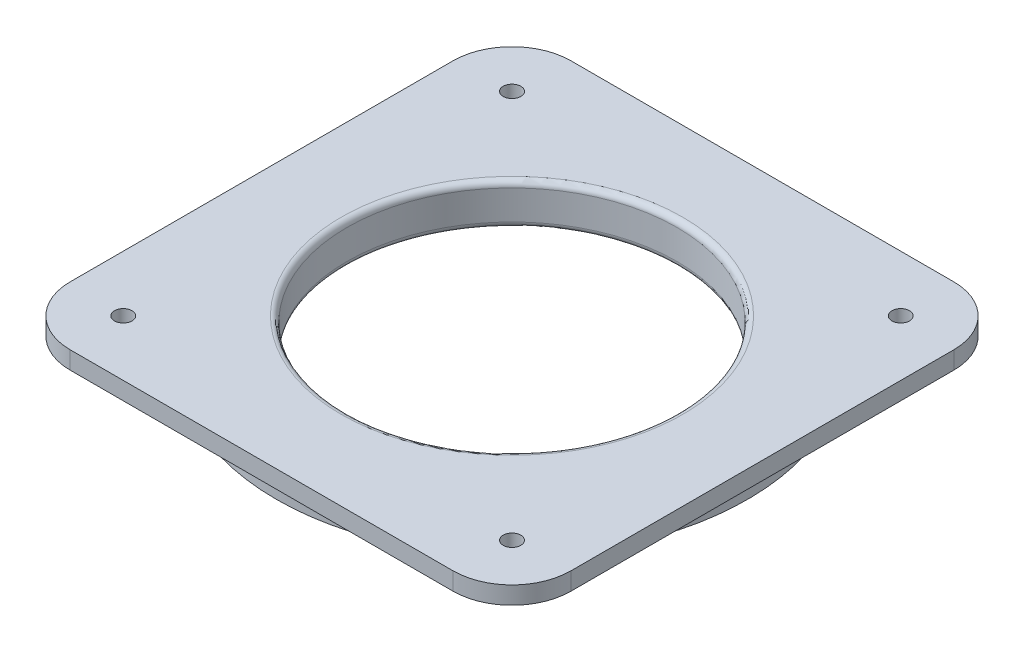
SolidWorks part; units mm, degrees
ref_plane "Plano frontal" through (0, 0, 0) normal (0, 0, 1) x (1, 0, 0)
ref_plane "Plano superior" through (0, 0, 0) normal (0, 1, 0) x (1, 0, 0)
ref_plane "Plano direito" through (0, 0, 0) normal (1, 0, 0) x (0, 0, -1)
ref_plane "Plano1" through (0, -3, 0) normal (0, -1, 0) x (1, 0, 0)
sketch "Esboço1" plane through (0, -3, 0) normal (0, -1, 0) x (1, 0, 0)
  line L0 (-42.5, 42.5) -> (-42.5, -42.5)
  line L1 (-42.5, -42.5) -> (42.5, -42.5)
  line L2 (42.5, -42.5) -> (42.5, 42.5)
  line L3 (42.5, 42.5) -> (-42.5, 42.5)
extrude "Ressalto-extrusão1" add sketch "Esboço1" against normal blind 3
ref_plane "Plano2" through (0, 0, 0) normal (0, 0, -1) x (-1, 0, 0)
sketch "Esboço2" plane through (0, 0, 0) normal (0, 0, -1) x (-1, 0, 0)
  line L0 (-40, -7) -> (0, -7)
  line L1 (0, -7) -> (0, -3)
  line L2 (0, -3) -> (-40, -3)
  line L3 (-40, -3) -> (-40, -7)
  line L4 (0, -7) -> (0, -3) construction
revolve "Revolução1" add sketch "Esboço2" angle 360 about L4
hole_wizard "Furo com folga de M521" positions "Esboço4" profile "Esboço3" hole size "M52" standard "Ansi Metric"
sketch "Esboço4" plane through (0, 0, 0) normal (0, 1, 0) x (1, 0, 0)
  point P0 (0, 0)
sketch "Esboço3" plane through (0, 0, 0) normal (1, 0, 0) x (0, 0, 1)
  line L0 (0, 0) -> (0, 7)
  line L1 (0, 7) -> (28, 7)
  line L2 (28, 7) -> (28, 0)
  line L5 (28, 0) -> (0, 0)
  line L11 (0, -6.35) -> (0, 107.95) construction
  dimension "Thru Hole Dia." = 56
  dimension "Thru Hole Depth" = 7
fillet "Filete1" radius 1 2 edges at (0, 0, 28) (0, -7, 28)
fillet "Filete2" radius 10 4 edges at (-42.5, -1.5, 42.5) (42.5, -1.5, 42.5) (-42.5, -1.5, -42.5) (42.5, -1.5, -42.5)
sketch "Esboço5" plane through (0, -3, 0) normal (0, -1, 0) x (1, 0, 0)
  line L0 (33, 0) -> (0, 0) construction
  line L1 (-33, -33) -> (33, -33) construction
  line L2 (-33, -33) -> (-33, 33) construction
  line L3 (-33, 33) -> (33, 33) construction
  line L4 (33, -33) -> (33, 33) construction
  line L5 (-33, -33) -> (33, 33) construction
  line L6 (-33, 33) -> (33, -33) construction
  line L7 (0, 0) -> (0, -33) construction
  circle A0 centre (33, 33) radius 1.5
  circle A1 centre (33, -33) radius 1.5
  circle A2 centre (-33, 33) radius 1.5
  circle A3 centre (-33, -33) radius 1.5
  point P0 (0, 0)
  dimension "D2" = 3
  dimension "D1" = 66
extrude "Corte-extrusão1" cut sketch "Esboço5" against normal blind 10
fillet "Filete3" radius 0.5 4 edges at (-33, -3, 34.5) (-33, -3, -34.5) (33, -3, -31.5) (33, -3, 31.5)
